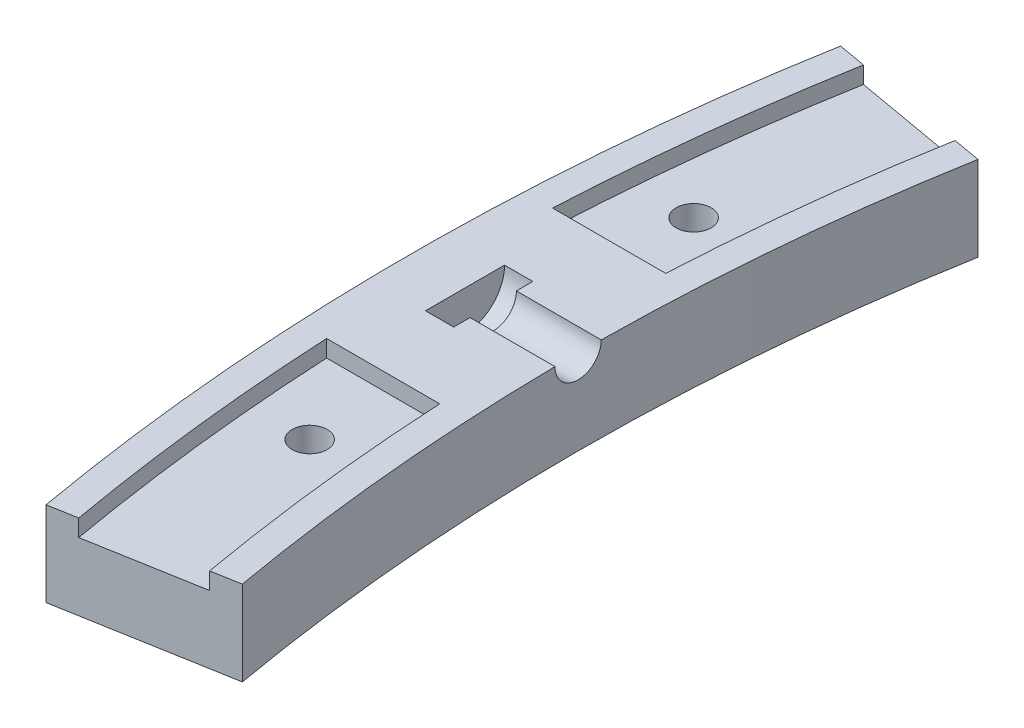
SolidWorks part; units mm, degrees
ref_plane "Front Plane" through (0, 0, 0) normal (0, 0, 1) x (1, 0, 0)
ref_plane "Top Plane" through (0, 0, 0) normal (0, 1, 0) x (1, 0, 0)
ref_plane "Right Plane" through (0, 0, 0) normal (1, 0, 0) x (0, 0, -1)
sketch "Sketch1" plane through (0, 0, 0) normal (0, 1, 0) x (1, 0, 0)
  line L0 (0, 0) -> (-199.4236, -35.1638) construction
  line L1 (0, 0) -> (-199.4236, 35.1638) construction
  line L2 (0, 0) -> (-195, 0) construction
  line L3 (-199.4236, 35.1638) -> (-184.6515, 32.559)
  line L4 (-184.6515, -32.559) -> (-199.4236, -35.1638)
  arc A0 (-196.9616, 34.7296) -> (-196.9616, -34.7296) centre (0, 0) ccw construction
  arc A1 (-187.1135, 32.9932) -> (-187.1135, -32.9932) centre (0, 0) ccw construction
  arc A2 (-192.0375, -33.8614) -> (-192.0375, 33.8614) centre (0, 0) cw construction
  arc A3 (-199.4236, 35.1638) -> (-199.4236, -35.1638) centre (0, 0) ccw
  arc A4 (-184.6515, 32.559) -> (-184.6515, -32.559) centre (0, 0) ccw
  dimension "D1" = 200
  dimension "D2" = 190
  dimension "D3" = 5
  dimension "D5" = 2.5
  dimension "D6" = 2.5
  dimension "D4" = 20
extrude "Boss-Extrude1" add sketch "Sketch1" along normal blind 7.5
sketch "Sketch2" plane through (0, 7.5, 0) normal (0, 1, 0) x (1, 0, 0)
  line L2 (0, 0) -> (-195, 0) construction
  line L3 (0, 0) -> (-199.4236, -35.1638) construction
  line L4 (0, 0) -> (-199.4236, 35.1638) construction
  line L5 (0, 0) -> (-190, 0) construction
  line L6 (0, 0) -> (-199.4236, -35.1638) construction
  line L7 (0, 0) -> (-199.4236, 35.1638) construction
  line L8 (0, 10) -> (-202.2529, 10) construction
  line L9 (0, 10) -> (0, -10) construction
  line L10 (0, -10) -> (-202.2529, -10) construction
  line L11 (-196.9616, 34.7296) -> (-187.1135, 32.9932)
  line L12 (-196.9616, -34.7296) -> (-187.1135, -32.9932)
  line L13 (-199.7498, -10) -> (-189.7367, -10)
  line L14 (-189.7367, 10) -> (-199.7498, 10)
  arc A0 (-196.9616, 34.7296) -> (-196.9616, -34.7296) centre (0, 0) ccw construction
  arc A1 (-187.1135, 32.9932) -> (-187.1135, -32.9932) centre (0, 0) ccw construction
  arc A2 (-196.9616, 34.7296) -> (-196.9616, -34.7296) centre (0, 0) ccw
  arc A3 (-187.1135, 32.9932) -> (-187.1135, -32.9932) centre (0, 0) ccw
  arc A4 (-199.4236, 35.1638) -> (-199.4236, -35.1638) centre (0, 0) ccw construction
  line M2 (-199.4236, -35.1638) -> (-184.6515, -32.559)
  line M4 (-184.6515, 32.559) -> (-199.4236, 35.1638)
  dimension "D1" = 20
extrude "Cut-Extrude1" cut sketch "Sketch2" against normal blind 1.5 contours A3 A2 L14 M4 | A3 L13 A2 M2
ref_plane "Plane1" through (-195, 0, 0) normal (1, 0, 0) x (0, 0, -1)
sketch "Sketch4" plane through (-195, 0, 0) normal (1, 0, 0) x (0, 0, -1)
  line L0 (32.559, 7.5) -> (-32.559, 7.5) construction
  circle A0 centre (0, 7.5) radius 3.5
  dimension "D1" = 7
extrude "Cut-Extrude3" cut sketch "Sketch4" against normal blind 2.5
sketch "Sketch5" plane through (-195, 0, 0) normal (1, 0, 0) x (0, 0, -1)
  line L0 (32.559, 7.5) -> (-32.559, 7.5) construction
  circle A0 centre (0, 7.5) radius 2.05
  dimension "D1" = 4.1
extrude "Cut-Extrude4" cut sketch "Sketch5" along normal through all
sketch "Sketch6" plane through (0, 0, 0) normal (0, -1, 0) x (1, 0, 0)
  line L0 (0, 0) -> (-194.258, 16.9954) construction
  line L1 (0, 0) -> (-195, 0) construction
  line L2 (0, 0) -> (-195, 0) construction
  line L3 (0, 0) -> (-194.258, -16.9954) construction
  arc A0 (-192.0375, 33.8614) -> (-192.0375, -33.8614) centre (0, 0) ccw construction
  dimension "D1" = 5
hole_wizard "Ø3.1 (3.1) Diameter Hole1" positions "Sketch7" profile "Sketch8" hole size "Ø3.1" standard "ISO" end condition through all
sketch "Sketch7" plane through (0, 0, 0) normal (0, -1, 0) x (-1, 0, 0)
  point P0 (194.258, -16.9954)
  point P3 (194.258, 16.9954)
sketch "Sketch8" plane through (-194.258, 0, 16.9954) normal (1, 0, 0) x (0, 0, -1)
  line L0 (0, 0) -> (0, 7.6156)
  line L1 (0, 7.6156) -> (1.55, 7.6156)
  line L2 (1.55, 7.6156) -> (1.55, 0)
  line L5 (1.55, 0) -> (0, 0)
  line L11 (0, -6.35) -> (0, 107.95) construction
  dimension "Thru Hole Dia." = 3.1
  dimension "Thru Hole Depth" = 7.6156
